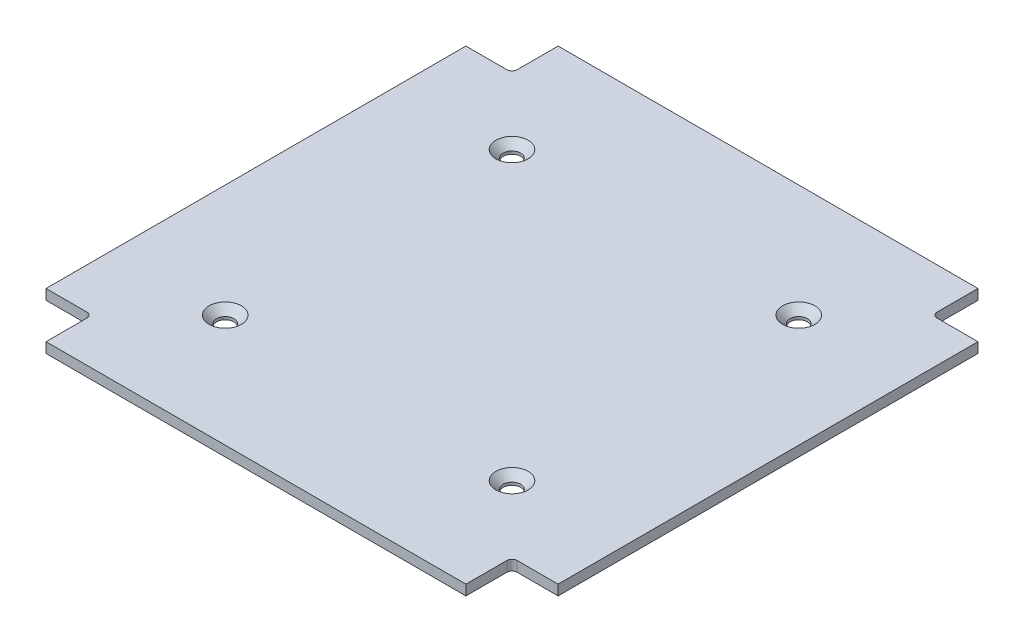
SolidWorks part; units mm, degrees
material "6061 Alloy"
ref_plane "Front Plane" through (0, 0, 0) normal (0, 0, 1) x (1, 0, 0)
ref_plane "Top Plane" through (0, 0, 0) normal (0, 1, 0) x (1, 0, 0)
ref_plane "Right Plane" through (0, 0, 0) normal (1, 0, 0) x (0, 0, -1)
sketch "Sketch1" plane through (0, 0, 0) normal (0, 1, 0) x (1, 0, 0)
  line L1 (-50, -50) -> (50, -50)
  line L2 (-50, -50) -> (-50, 50)
  line L3 (-50, 50) -> (50, 50)
  line L4 (50, -50) -> (50, 50)
  line L5 (-50, -50) -> (50, 50) construction
  line L6 (-50, 50) -> (50, -50) construction
  point P0 (0, 0)
  dimension "D1" = 100
  dimension "D2" = 100
extrude "Base Extrusion" add sketch "Sketch1" along normal blind 2
sketch "Sketch2" plane through (0, 2, 0) normal (0, 1, 0) x (1, 0, 0)
  line L1 (50, -50) -> (50, 50) construction
  line L5 (50, 41) -> (41, 41)
  line L8 (41, 41) -> (41, 50)
  line L9 (50, 50) -> (-50, 50) construction
  line L10 (41, 50) -> (50, 50)
  line L11 (50, 50) -> (50, 41)
  line L16 (0, 0) -> (0, 21.7531) construction
  line L17 (0, 0) -> (21.8877, 0) construction
  line L22 (-50, 50) -> (-50, 41)
  line L23 (-41, 50) -> (-50, 50)
  line L24 (-41, 41) -> (-41, 50)
  line L27 (-50, 41) -> (-41, 41)
  line L36 (-50, -41) -> (-41, -41)
  line L39 (-41, -41) -> (-41, -50)
  line L40 (-41, -50) -> (-50, -50)
  line L41 (-50, -50) -> (-50, -41)
  line L50 (50, -50) -> (50, -41)
  line L51 (41, -50) -> (50, -50)
  line L52 (41, -41) -> (41, -50)
  line L55 (50, -41) -> (41, -41)
  dimension "D1" = 9
  dimension "D2" = 9
extrude "Corner Cutouts" cut sketch "Sketch2" against normal through all
hole_wizard "CSK for M3 Flat Head Machine Screw1" [suppressed] positions "Sketch4" profile "Sketch3" countersink size "M3" standard "Ansi Metric"
sketch "Sketch4" plane through (0, 2, 0) normal (0, 1, 0) x (-1, 0, 0)
  line L4 (-50, 41) -> (-50, -41) construction
  line L5 (-41, -50) -> (41, -50) construction
  line L6 (50, -41) -> (50, 41) construction
  line L7 (41, 50) -> (-41, 50) construction
  point P3 (-44.5, 0)
  point P5 (0, 44.5)
  point P7 (0, -44.5)
  point P9 (44.5, 0)
  dimension "D1" = 5.5
  dimension "D2" = 5.5
  dimension "D3" = 5.5
  dimension "D4" = 5.5
sketch "Sketch3" plane through (44.5, 2, 0) normal (1, 0, 0) x (0, 0, 1)
  line L0 (0, 0) -> (0, 11.0215)
  line L1 (0, 11.0215) -> (1.7, 10)
  line L2 (1.7, 10) -> (1.7, 1.45)
  line L3 (1.7, 1.45) -> (3.15, 0)
  line L5 (3.15, 0) -> (0, 0)
  line L6 (-1.7, 1.45) -> (-3.15, 0) construction
  line L10 (0, 11.0215) -> (-1.7, 10) construction
  line L11 (0, -6.35) -> (0, 107.95) construction
  dimension "Hole Dia." = 3.4
  dimension "Hole Depth" = 10
  dimension "Near C'Sink Dia." = 6.3
  dimension "Near C'Sink Angle" = 90
  dimension "Drill Angle" = 118
sketch "Sketch5" plane through (0, 0, 0) normal (0, -1, 0) x (1, 0, 0)
  line L0 (-31, 31) -> (-41, 31)
  line L1 (41, 41) -> (31, 41)
  line L2 (41, 41) -> (41, 31)
  line L3 (41, 31) -> (31, 31)
  line L4 (31, 41) -> (31, 31)
  line L5 (-41, 41) -> (-41, 31)
  line L6 (-31, 41) -> (-41, 41)
  line L7 (-31, 41) -> (-31, 31)
  line L8 (41, -41) -> (31, -41)
  line L9 (31, -31) -> (31, -41)
  line L10 (41, -31) -> (31, -31)
  line L11 (41, -31) -> (41, -41)
  line L12 (-31, -41) -> (-41, -41)
  line L13 (-41, -31) -> (-41, -41)
  line L14 (-31, -31) -> (-41, -31)
  line L15 (-31, -31) -> (-31, -41)
  line L16 (41, 31) -> (-31, 31) construction
  dimension "D1" = 10
  dimension "D2" = 10
  dimension "D5" = 72
  dimension "D6" = 72
  dimension "D3" = 2
  dimension "D4" = 2
extrude "PCB Mounts" [suppressed] add sketch "Sketch5" along normal blind 4
hole_wizard "M3x0.5 Tapped Holes For PCBs" [suppressed] positions "Sketch7" profile "Sketch6" tap size "M3x0.5" standard "Ansi Metric"
sketch "Sketch7" [suppressed] plane through (0, -4, 0) normal (0, -1, 0) x (1, 0, 0)
  line L0 (-31, 31) -> (-31, 41) construction
  line L1 (31, -31) -> (31, -41) construction
  line L2 (41, -31) -> (31, -31) construction
  line L3 (-41, 31) -> (-31, 31) construction
  point P0 (-36, 36)
  point P1 (36, 36)
  point P3 (36, -36)
  point P5 (-36, -36)
  dimension "D1" = 5
  dimension "D2" = 5
  dimension "D3" = 5
  dimension "D4" = 5
cosmetic thread "Hole Thread1" parameters "D2"=3
cosmetic thread "Hole Thread2" parameters "D2"=3
cosmetic thread "Hole Thread3" parameters "D2"=3
cosmetic thread "Hole Thread4" parameters "D2"=3
sketch "Sketch6" plane through (-36, -4, 36) normal (1, 0, 0) x (0, 0, -1)
  line L0 (0, 0) -> (0, 6)
  line L1 (0, 6) -> (1.25, 6)
  line L2 (1.25, 6) -> (1.25, 0)
  line L5 (1.25, 0) -> (0, 0)
  line L11 (0, -6.35) -> (0, 107.95) construction
  dimension "Thru Tap Drill Dia." = 2.5
  dimension "Thru Tap Drill Depth" = 6
hole_wizard "CSK for M3 Flat Head Machine Screw2" positions "Sketch9" profile "Sketch10" countersink size "M3" standard "Ansi Metric" end condition through all
sketch "Sketch9" plane through (0, 2, 0) normal (0, 1, 0) x (-1, 0, 0)
  line L0 (50, -41) -> (50, 41) construction
  line L1 (41, 50) -> (-41, 50) construction
  line L2 (-50, 41) -> (-50, -41) construction
  line L3 (-41, -50) -> (41, -50) construction
  point P0 (28, 28)
  point P1 (28, -28)
  point P3 (-28, -28)
  point P5 (-28, 28)
  dimension "D1" = 22
  dimension "D2" = 22
  dimension "D3" = 22
  dimension "D4" = 22
sketch "Sketch10" plane through (-28, 2, 28) normal (1, 0, 0) x (0, 0, 1)
  line L0 (0, 0) -> (0, 2)
  line L1 (0, 2) -> (1.7, 2)
  line L2 (1.7, 2) -> (1.7, 1.45)
  line L3 (1.7, 1.45) -> (3.15, 0)
  line L5 (3.15, 0) -> (0, 0)
  line L6 (-1.7, 1.45) -> (-3.15, 0) construction
  line L11 (0, -6.35) -> (0, 107.95) construction
  dimension "Thru Hole Dia." = 3.4
  dimension "Thru Hole Depth" = 2
  dimension "Near C'Sink Dia." = 6.3
  dimension "Near C'Sink Angle" = 90
fillet "Fillet For Rails" radius 1 4 edges at (-41, 1, -41) (41, 1, -41) (-41, 1, 41) (41, 1, 41)
sketch "Sketch11" plane through (0, 2, 0) normal (0, 1, 0) x (1, 0, 0)
  line L1 (-31.0531, 8.4169) -> (-9.0531, 8.4169)
  line L2 (-32.5531, 9.9169) -> (-32.5531, 31.9169)
  line L3 (-31.0531, 33.4169) -> (-9.0531, 33.4169)
  line L4 (-7.5531, 9.9169) -> (-7.5531, 31.9169)
  arc A0 (-32.5531, 31.9169) -> (-31.0531, 33.4169) centre (-31.0531, 31.9169) cw
  arc A1 (-9.0531, 33.4169) -> (-7.5531, 31.9169) centre (-9.0531, 31.9169) cw
  arc A2 (-9.0531, 8.4169) -> (-7.5531, 9.9169) centre (-9.0531, 9.9169) ccw
  arc A3 (-31.0531, 8.4169) -> (-32.5531, 9.9169) centre (-31.0531, 9.9169) cw
  dimension "D1" = 1.5
  dimension "D2" = 25
  dimension "D3" = 25
extrude "GPS Antenna Hole" [suppressed] cut sketch "Sketch11" against normal through all
